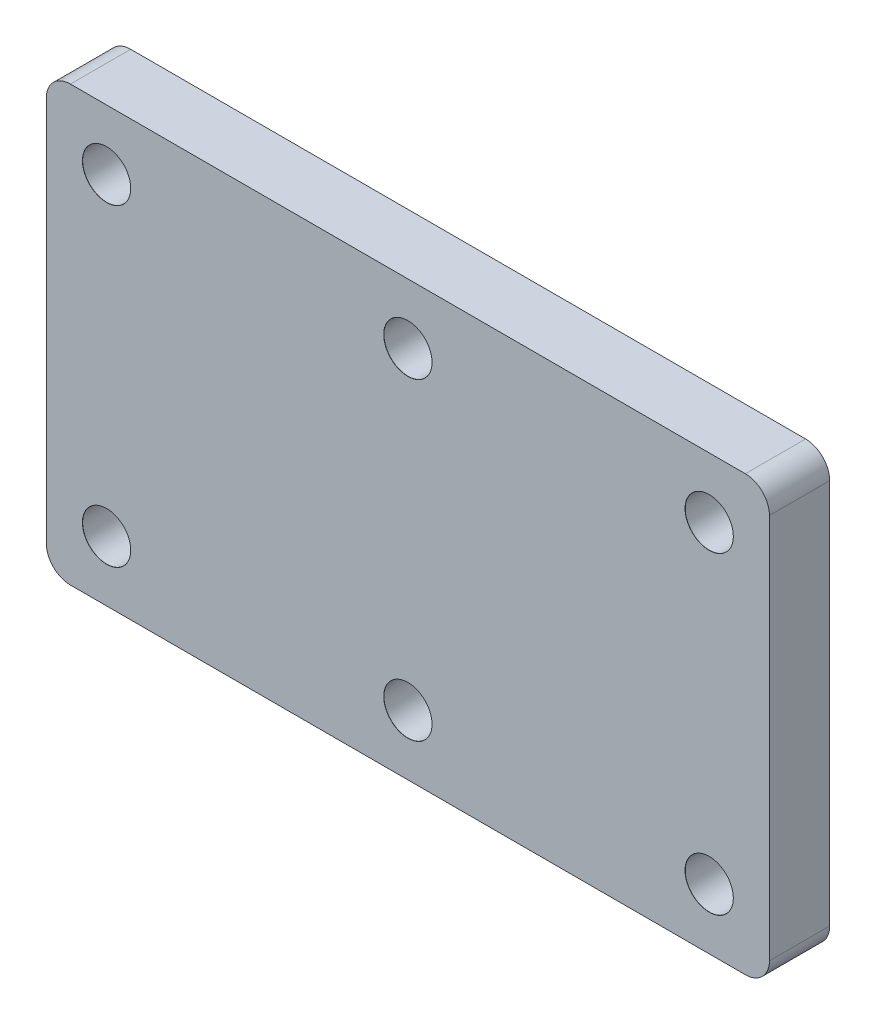
SolidWorks part; units mm, degrees
ref_plane "Front Plane" through (0, 0, 0) normal (0, 0, 1) x (1, 0, 0)
ref_plane "Top Plane" through (0, 0, 0) normal (0, 1, 0) x (1, 0, 0)
ref_plane "Right Plane" through (0, 0, 0) normal (1, 0, 0) x (0, 0, -1)
sketch "Sketch3" plane through (0, 0, 0) normal (0, 0, 1) x (1, 0, 0)
  line L0 (-125, 90) -> (-125, 65) construction
  line L1 (150, -90) -> (-150, -90)
  line L2 (150, -90) -> (150, 90)
  line L3 (150, 90) -> (-150, 90)
  line L4 (-150, -90) -> (-150, 90)
  line L5 (150, -90) -> (-150, 90) construction
  line L6 (150, 90) -> (-150, -90) construction
  circle A0 centre (-125, 65) radius 10
  circle A1 centre (-125, -65) radius 10
  circle A2 centre (0, 65) radius 10
  circle A3 centre (0, -65) radius 10
  circle A4 centre (125, 65) radius 10
  circle A5 centre (125, -65) radius 10
  point P0 (0, 0)
  point P19 (0, 0)
  point P20 (0, -90)
  point P21 (125.3104, 90)
  point P22 (121.6542, 81.6014)
  point P23 (122.6513, -90)
  dimension "D5" = 20
  dimension "D7" = 20
  dimension "D8" = 20
  dimension "D9" = 20
  dimension "D10" = 20
  dimension "D11" = 20
  dimension "D1" = 300
  dimension "D2" = 180
  dimension "D3" = 25
  dimension "D4" = 25
  dimension "D6" = 25
  dimension "D12" = 25
  dimension "D13" = 25
  dimension "D14" = 25
  dimension "D15" = 25
  dimension "D16" = 25
extrude "Boss-Extrude2" add sketch "Sketch3" along normal blind 25
fillet "Fillet1" radius 10 1 edges at (-150, 90, 12.5)
fillet "Fillet2" radius 10 3 edges at (150, 90, 12.5) (150, -90, 12.5) (-150, -90, 12.5)
hole_wizard "Ø20.0mm Dowel Hole3" positions "3DSketch3" profile "Sketch7" hole size "Ø20.0" standard "BSI"
sketch3d "3DSketch3"
  line L0 (-125, 65, 25) -> (-125, 65, 0) construction
  point P0 (-125, 65, 25)
sketch "Sketch7" plane through (-125, 65, 25) normal (1, 0, 0) x (0, -1, 0)
  line L0 (0, 0) -> (0, 33.0136)
  line L1 (0, 33.0136) -> (10, 27.005)
  line L2 (10, 27.005) -> (10, 0.0604)
  line L3 (10, 0.0604) -> (10.025, 0)
  line L5 (10.025, 0) -> (0, 0)
  line L6 (-10, 0.0604) -> (-10.025, 0) construction
  line L10 (0, 33.0136) -> (-10, 27.005) construction
  line L11 (0, -6.35) -> (0, 107.95) construction
  dimension "Hole Dia." = 20
  dimension "Hole Depth" = 27.005
  dimension "Near C'Sink Dia." = 20.05
  dimension "Near C'Sink Angle" = 45
  dimension "Drill Angle" = 118
mirror "Mirror2" about plane through (0, 0, 25) normal (0, 0, 1) of "Ø20.0mm Dowel Hole3"
hole_wizard "Ø20.0mm Dowel Hole4" positions "3DSketch5" profile "Sketch9" hole size "Ø20.0" standard "BSI"
sketch3d "3DSketch5"
  line L0 (-125, 65, 25) -> (-125, 65, 24.9396) construction
  line L1 (-125, -65, 25) -> (-125, -65, 0) construction
  line L2 (0, 65, 25) -> (0, 65, 0) construction
  line L3 (0, -65, 25) -> (0, -65, 0) construction
  line L4 (125, -65, 25) -> (125, -65, 0) construction
  line L5 (125, 65, 25) -> (125, 65, 0) construction
  point P0 (-125, 65, 25)
  point P4 (-125, -65, 25)
  point P8 (0, 65, 25)
  point P12 (0, -65, 25)
  point P16 (125, -65, 25)
  point P20 (125, 65, 25)
sketch "Sketch9" plane through (-125, 65, 25) normal (1, 0, 0) x (0, -1, 0)
  line L0 (0, 0) -> (0, 33.0136)
  line L1 (0, 33.0136) -> (10, 27.005)
  line L2 (10, 27.005) -> (10, 0.0604)
  line L3 (10, 0.0604) -> (10.025, 0)
  line L5 (10.025, 0) -> (0, 0)
  line L6 (-10, 0.0604) -> (-10.025, 0) construction
  line L10 (0, 33.0136) -> (-10, 27.005) construction
  line L11 (0, -6.35) -> (0, 107.95) construction
  dimension "Hole Dia." = 20
  dimension "Hole Depth" = 27.005
  dimension "Near C'Sink Dia." = 20.05
  dimension "Near C'Sink Angle" = 45
  dimension "Drill Angle" = 118
